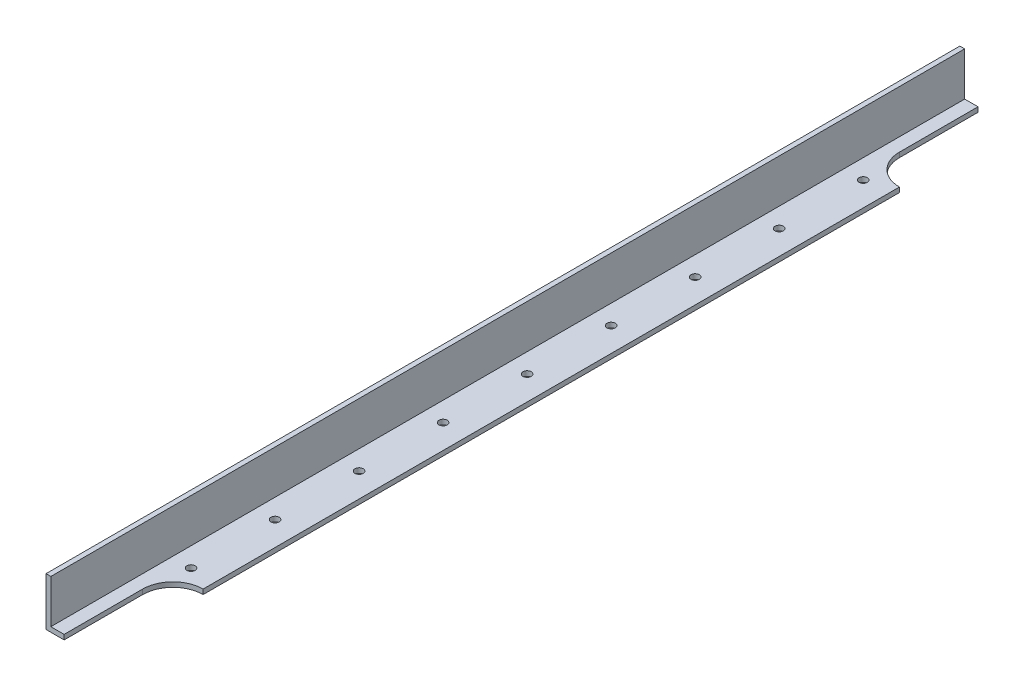
SolidWorks part; units mm, degrees
material "Д16Т ГОСТ 4784-74"
ref_plane "Спереди" through (0, 0, 0) normal (0, 0, 1) x (1, 0, 0)
ref_plane "Сверху" through (0, 0, 0) normal (0, 1, 0) x (1, 0, 0)
ref_plane "Справа" through (0, 0, 0) normal (1, 0, 0) x (0, 0, -1)
sketch "Эскиз1" plane through (0, 0, 0) normal (0, 0, 1) x (1, 0, 0)
  line L0 (0, 0) -> (0, 20)
  line L1 (0, 0) -> (20, 0)
  dimension "D1" = 20
  dimension "D2" = 20
extrude "Вытянуть-Тонкостенный1" add sketch "Эскиз1" along normal blind 378 thin
sketch "Эскиз2" plane through (0, 2, 0) normal (0, 1, 0) x (1, 0, 0)
  line L0 (20, -189) -> (0, -189) construction
  line L1 (20, -378) -> (20, 0) construction
  line L2 (0, -378) -> (0, 0) construction
  line L3 (7.5, -378) -> (7.5, -345.5)
  line L4 (20, 0) -> (7.5, 0)
  line L5 (20, 0) -> (20, -45)
  line L6 (20, -378) -> (20, -333)
  line L7 (7.5, 0) -> (7.5, -32.5)
  line L8 (20, -378) -> (7.5, -378)
  arc A0 (7.5, -32.5) -> (20, -45) centre (20, -32.5) ccw
  arc A1 (7.5, -345.5) -> (20, -333) centre (20, -345.5) cw
  dimension "D1" = 45
  dimension "D2" = 7.5
extrude "Вырез-Вытянуть1" cut sketch "Эскиз2" against normal through all
hole_wizard "Отверстие с зазором M31" positions "Эскиз4" profile "Эскиз3" hole size "M3" standard "DIN"
sketch "Эскиз4" plane through (0, 0, 0) normal (0, -1, 0) x (1, 0, 0)
  line L0 (0, 0) -> (7.5, 0) construction
  line L1 (0, 378) -> (0, 0) construction
  line L2 (10, 50) -> (10, 84.75) construction
  point P0 (10, 50)
  point P9 (10, 84.75)
  point P10 (10, 119.5)
  point P11 (10, 154.25)
  point P12 (10, 189)
  point P13 (10, 223.75)
  point P14 (10, 258.5)
  point P15 (10, 293.25)
  point P16 (10, 328)
  dimension "D1" = 50
  dimension "D2" = 10
  dimension "D3" = 34.75
sketch "Эскиз3" plane through (10, 0, 50) normal (1, 0, 0) x (0, 0, -1)
  line L0 (0, 0) -> (0, 6.0215)
  line L1 (0, 6.0215) -> (1.7, 5)
  line L2 (1.7, 5) -> (1.7, 0)
  line L5 (1.7, 0) -> (0, 0)
  line L10 (0, 6.0215) -> (-1.7, 5) construction
  line L11 (0, -6.35) -> (0, 107.95) construction
  dimension "Диаметр отверстия" = 3.4
  dimension "Глубина отверстия" = 5
  dimension "Угол заточки сверла" = 118
